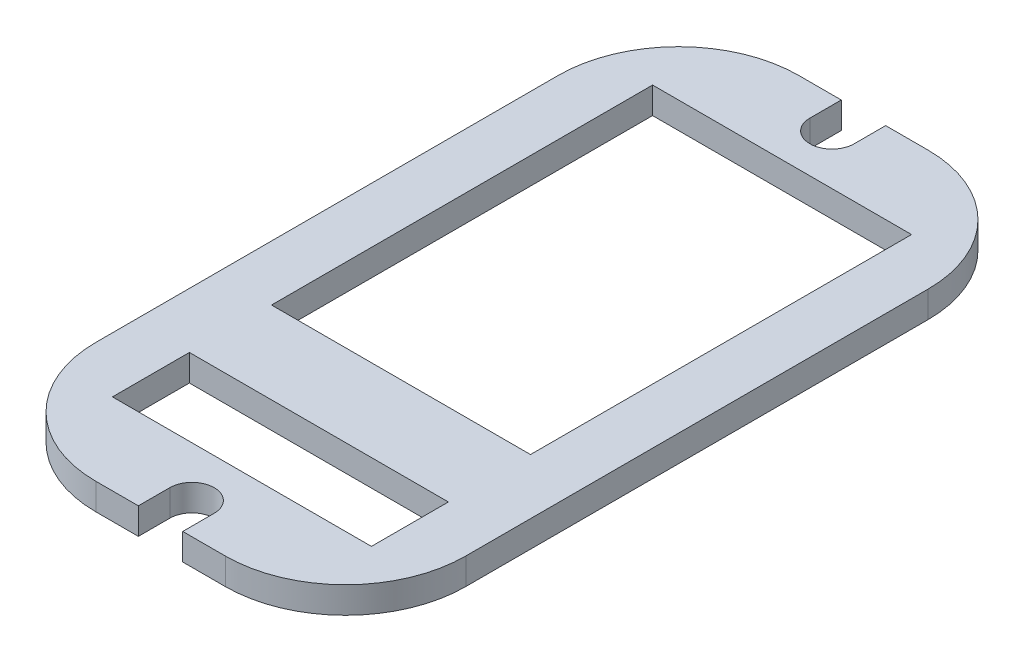
SolidWorks part; units mm, degrees
ref_plane "Front Plane" through (0, 0, 0) normal (0, 0, 1) x (1, 0, 0)
ref_plane "Top Plane" through (0, 0, 0) normal (0, 1, 0) x (1, 0, 0)
ref_plane "Right Plane" through (0, 0, 0) normal (1, 0, 0) x (0, 0, -1)
sketch "Sketch2" plane through (0, 0, 0) normal (0, 1, 0) x (1, 0, 0)
  line L0 (-0.6, 9.5) -> (-1.75, 9.5)
  line L1 (-5, 6.25) -> (-5, -6.25)
  line L2 (-1.75, -9.5) -> (-0.6, -9.5)
  line L3 (-3.5, -3) -> (3.5, -3)
  line L4 (3.5, -3) -> (3.5, 7.3)
  line L5 (3.5, 7.3) -> (-3.5, 7.3)
  line L6 (-3.5, 7.3) -> (-3.5, -3)
  line L7 (-3.5, -7.3) -> (3.5, -7.3)
  line L8 (3.5, -7.3) -> (3.5, -5.22)
  line L9 (3.5, -5.22) -> (-3.5, -5.22)
  line L10 (-3.5, -5.22) -> (-3.5, -7.3)
  line L11 (0, 8.65) -> (0, -8.65) construction
  line L12 (-0.6, -8.65) -> (-0.6, -9.5)
  line L13 (0.6, -8.65) -> (0.6, -9.5)
  line L14 (-0.6, 9.5) -> (-0.6, 8.65)
  line L15 (0.6, -9.5) -> (1.75, -9.5)
  line L16 (5, -6.25) -> (5, 6.25)
  line L17 (1.75, 9.5) -> (0.6, 9.5)
  line L18 (0, 0) -> (0, -3) construction
  line L19 (0, -3) -> (0, -5.22) construction
  line L20 (0.6, 9.5) -> (0.6, 8.65)
  arc A0 (-0.6, 8.65) -> (0.6, 8.65) centre (0, 8.65) ccw
  arc A1 (0.6, -8.65) -> (-0.6, -8.65) centre (0, -8.65) ccw
  arc A2 (-1.75, 9.5) -> (-5, 6.25) centre (-1.75, 6.25) ccw
  arc A3 (-5, -6.25) -> (-1.75, -9.5) centre (-1.75, -6.25) ccw
  arc A4 (1.75, -9.5) -> (5, -6.25) centre (1.75, -6.25) ccw
  arc A5 (5, 6.25) -> (1.75, 9.5) centre (1.75, 6.25) ccw
  point P30 (0, -5.22)
  point P31 (0, -3)
  point P38 (0, 0)
  dimension "D7" = 0.6
  dimension "D9" = 3.25
  dimension "D1" = 2.22
  dimension "D2" = 3
  dimension "D3" = 10.3
  dimension "D4" = 2.08
  dimension "D5" = 17.3
  dimension "D6" = 7
  dimension "D8" = 10
  dimension "D10" = 19
extrude "Boss-Extrude1" add sketch "Sketch2" along normal blind 0.716
